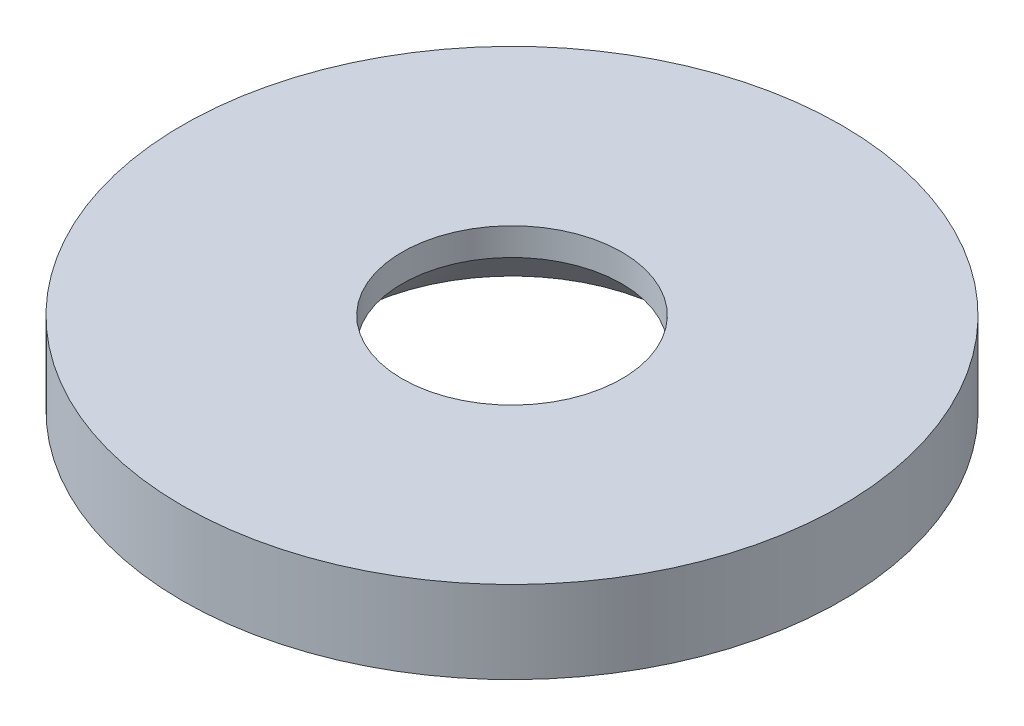
SolidWorks part; units mm, degrees
ref_plane "Спереди" through (0, 0, 0) normal (0, 0, 1) x (1, 0, 0)
ref_plane "Сверху" through (0, 0, 0) normal (0, 1, 0) x (1, 0, 0)
ref_plane "Справа" through (0, 0, 0) normal (1, 0, 0) x (0, 0, -1)
sketch "Эскиз1" plane through (0, 0, 0) normal (0, 1, 0) x (1, 0, 0)
  circle A0 centre (0, 0) radius 6
  circle A1 centre (0, 0) radius 2
  dimension "D1" = 12
  dimension "D2" = 4
extrude "Бобышка-Вытянуть1" add sketch "Эскиз1" along normal blind 1.5
sketch3d "Трехмерный эскиз1" [suppressed]
  line L0 (2, 2, 0) -> (1.75, 2.433, 0)
  line L1 (1.75, 2.433, 0) -> (2.616, 2.933, 0)
  line L2 (2.616, 2.933, 0) -> (3.1547, 2, 0)
  line L3 (3.1547, 2, 0) -> (2, 2, 0)
  line L4 (2, 2, 0) -> (0, 2, 0) construction
  line L5 (0, 2, 0) -> (0, 0, 0) construction
  circle A0 centre (0, 2, 0) radius 2 construction
  point P4 (0, 4, 0)
  dimension "D1" = 60
  dimension "D2" = 1
  dimension "D3" = 1.75
chamfer "Фаска1" distance 1 angle 45 1 edges at (0, 0, 2)
